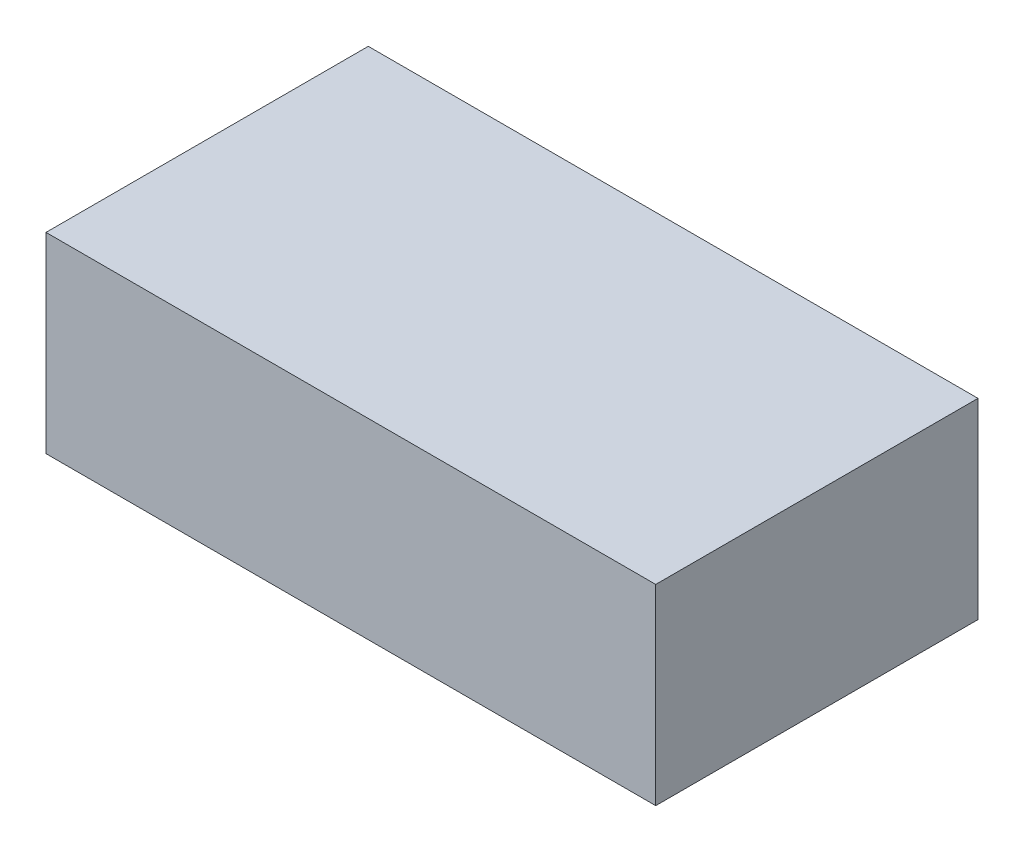
SolidWorks part; units mm, degrees
ref_plane "Front Plane" through (0, 0, 0) normal (0, 0, 1) x (1, 0, 0)
ref_plane "Top Plane" through (0, 0, 0) normal (0, 1, 0) x (1, 0, 0)
ref_plane "Right Plane" through (0, 0, 0) normal (1, 0, 0) x (0, 0, -1)
sketch "Sketch1" plane through (0, 0, 0) normal (0, 1, 0) x (1, 0, 0)
  line L1 (-35, 18.5) -> (35, 18.5)
  line L2 (-35, 18.5) -> (-35, -18.5)
  line L3 (-35, -18.5) -> (35, -18.5)
  line L4 (35, 18.5) -> (35, -18.5)
  line L5 (-35, 18.5) -> (35, -18.5) construction
  line L6 (-35, -18.5) -> (35, 18.5) construction
  point P0 (0, 0)
  dimension "D1" = 70
  dimension "D2" = 37
extrude "Boss-Extrude1" add sketch "Sketch1" along normal blind 22
